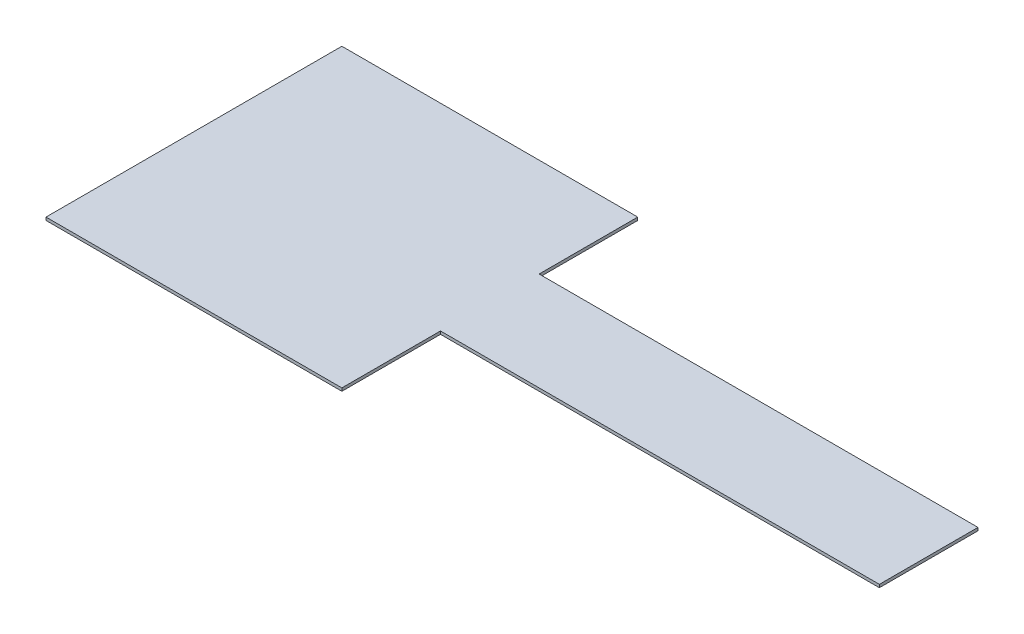
SolidWorks part; units mm, degrees
ref_plane "Front Plane" through (0, 0, 0) normal (0, 0, 1) x (1, 0, 0)
ref_plane "Top Plane" through (0, 0, 0) normal (0, 1, 0) x (1, 0, 0)
ref_plane "Right Plane" through (0, 0, 0) normal (1, 0, 0) x (0, 0, -1)
sketch "Sketch1" plane through (0, 0, 0) normal (0, 1, 0) x (1, 0, 0)
  line L2 (0, -15) -> (30, -15)
  line L3 (30, -15) -> (30, -5)
  line L4 (30, -5) -> (74.5, -5)
  line L5 (74.5, 5) -> (74.5, -5)
  line L6 (0, 15) -> (30, 15)
  line L7 (30, 15) -> (30, 5)
  line L8 (30, 5) -> (74.5, 5)
  line L9 (0, 15) -> (0, -15)
  line L10 (0, 0) -> (74.5, 0) construction
  dimension "D1" = 30
  dimension "D2" = 30
  dimension "D3" = 30
  dimension "D4" = 10
  dimension "D5" = 10
  dimension "D6" = 44.5
  dimension "D7" = 5
extrude "Boss-Extrude1" add sketch "Sketch1" against normal blind 0.3 and the other way blind 0.0001
